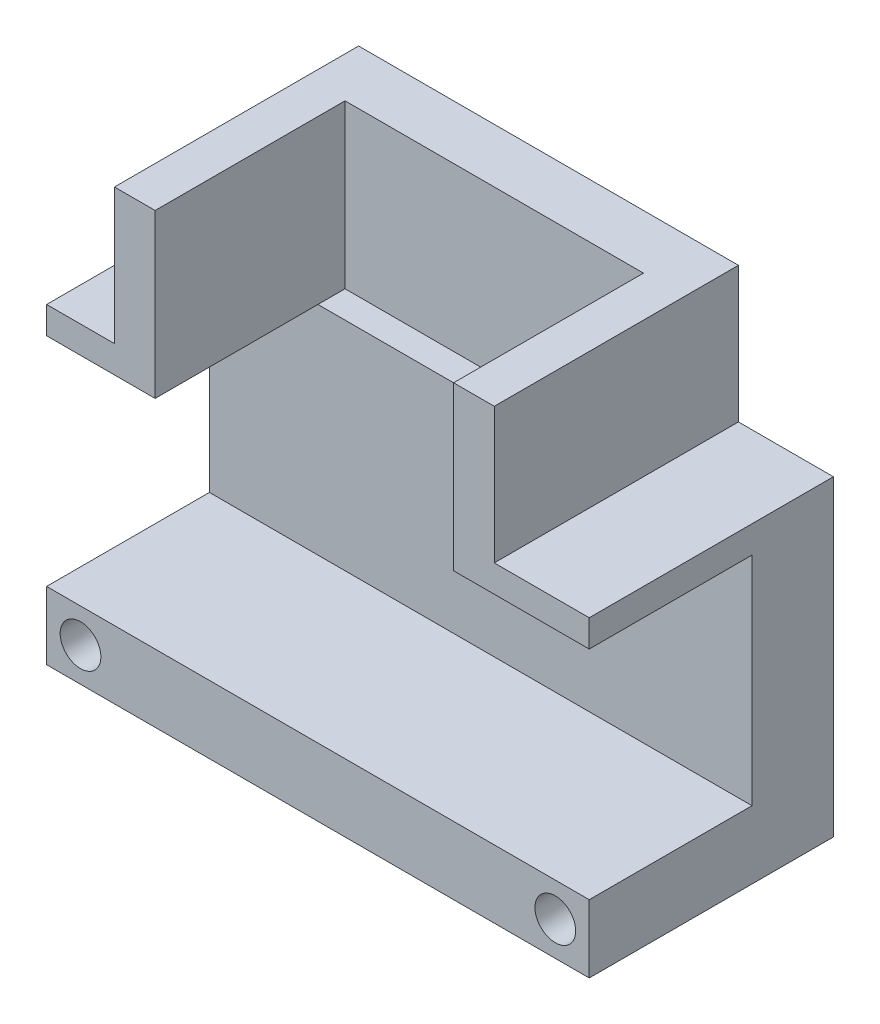
SolidWorks part; units mm, degrees
ref_plane "Alzado" through (0, 0, 0) normal (0, 0, 1) x (1, 0, 0)
ref_plane "Planta" through (0, 0, 0) normal (0, 1, 0) x (1, 0, 0)
ref_plane "Vista lateral" through (0, 0, 0) normal (1, 0, 0) x (0, 0, -1)
sketch "Croquis1" plane through (0, 0, 0) normal (0, 0, 1) x (1, 0, 0)
  line L1 (-49.2774, 8.4286) -> (-49.2774, -14.5714)
  line L2 (-49.2774, -14.5714) -> (-9.2774, -14.5714)
  line L4 (-9.2774, -14.5714) -> (-9.2774, 8.4286)
  line L5 (-9.2774, 8.4286) -> (-16.2774, 8.4286)
  line L6 (-16.2774, 8.4286) -> (-16.2774, 18.4286)
  line L7 (-16.2774, 18.4286) -> (-44.2774, 18.4286)
  line L8 (-44.2774, 18.4286) -> (-44.2774, 8.4286)
  line L9 (-44.2774, 8.4286) -> (-49.2774, 8.4286)
  dimension "D1" = 23
  dimension "D2" = 40
  dimension "D3" = 7
  dimension "D4" = 10
  dimension "D6" = 5
extrude "Saliente-Extruir1" add sketch "Croquis1" along normal blind 18
sketch "Croquis2" plane through (0, 0, 18) normal (0, 0, 1) x (1, 0, 0)
  line L0 (-9.2774, 6.4286) -> (-9.2774, -9.5714)
  line L4 (-49.2774, -9.5714) -> (-49.2774, 6.4286)
  line L5 (-49.2774, 6.4286) -> (-41.2774, 6.4286)
  line L6 (-41.2774, 6.4286) -> (-41.2774, 18.4286)
  line L7 (-16.2774, 18.4286) -> (-44.2774, 18.4286) construction
  line L8 (-41.2774, 18.4286) -> (-19.2774, 18.4286)
  line L9 (-19.2774, 18.4286) -> (-19.2774, 6.4286)
  line L13 (-9.2774, -14.5714) -> (-9.2774, 8.4286) construction
  line L14 (-9.2774, 6.4286) -> (-19.2774, 6.4286)
  line L15 (-49.2774, 8.4286) -> (-49.2774, -14.5714) construction
  line L16 (-49.2774, -9.5714) -> (-9.2774, -9.5714)
  dimension "D1" = 16
  dimension "D2" = 8
  dimension "D3" = 12
  dimension "D4" = 22
  dimension "D5" = 16
extrude "Cortar-Extruir1" cut sketch "Croquis2" against normal blind 14
sketch "Croquis3" plane through (0, 0, 4) normal (0, 0, 1) x (1, 0, 0)
  line L1 (-49.2774, 6.4286) -> (-9.2774, 6.4286)
  line L2 (-49.2774, 6.4286) -> (-49.2774, -9.5714)
  line L3 (-49.2774, -9.5714) -> (-9.2774, -9.5714)
  line L4 (-9.2774, 6.4286) -> (-9.2774, -9.5714)
extrude "Saliente-Extruir2" add sketch "Croquis3" along normal blind 2
sketch "Croquis10" plane through (0, 0, 18) normal (0, 0, 1) x (1, 0, 0)
  line L0 (-49.2774, -14.5714) -> (-9.2774, -14.5714) construction
  line L2 (-49.2774, -9.5714) -> (-49.2774, -14.5714) construction
  circle A0 centre (-46.7774, -12.0714) radius 1.5
  circle A1 centre (-11.7774, -12.0714) radius 1.5
  dimension "D1" = 2.5
  dimension "D2" = 2.5
  dimension "D3" = 2
extrude "Cortar-Extruir2" cut sketch "Croquis10" against normal blind 10
